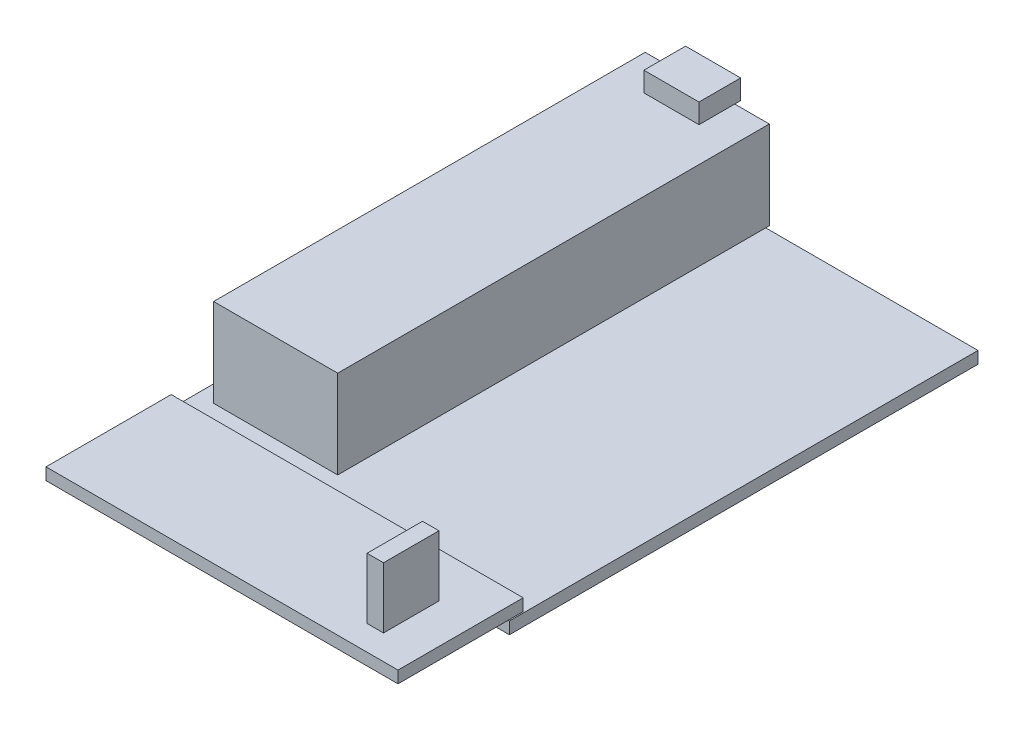
SolidWorks part; units mm, degrees
ref_plane "Front Plane" through (0, 0, 0) normal (0, 0, 1) x (1, 0, 0)
ref_plane "Top Plane" through (0, 0, 0) normal (0, 1, 0) x (1, 0, 0)
ref_plane "Right Plane" through (0, 0, 0) normal (1, 0, 0) x (0, 0, -1)
sketch "Sketch1" plane through (0, 0, 0) normal (0, 1, 0) x (1, 0, 0)
  line L1 (-42.6133, 31.1958) -> (7.5517, 31.1958)
  line L2 (-42.6133, 31.1958) -> (-42.6133, -35.3522)
  line L3 (-42.6133, -35.3522) -> (7.5517, -35.3522)
  line L4 (7.5517, 31.1958) -> (7.5517, -35.3522)
  dimension "D1" = 50.165
  dimension "D2" = 66.548
extrude "Boss-Extrude1" add sketch "Sketch1" along normal blind 1.7
sketch "Sketch2" plane through (0, 1.7, 0) normal (0, 1, 0) x (1, 0, 0)
  line L0 (-42.6133, 31.1958) -> (-42.6133, -35.3522) construction
  line L1 (-42.6133, -33.2186) -> (7.3751, -33.2186)
  line L2 (-42.6133, -33.2186) -> (-42.6133, -50.9986)
  line L3 (-42.6133, -50.9986) -> (7.3751, -50.9986)
  line L4 (7.3751, -33.2186) -> (7.3751, -50.9986)
  line L5 (-42.6133, -35.3522) -> (7.5517, -35.3522) construction
  dimension "D1" = 17.78
  dimension "D2" = 2.1336
extrude "Boss-Extrude2" add sketch "Sketch2" along normal blind 1.7
sketch "Sketch3" plane through (0, 1.7, 0) normal (0, 1, 0) x (1, 0, 0)
  line L0 (-42.6133, 31.1958) -> (-42.6133, -33.2186) construction
  line L1 (-40.2257, 31.7038) -> (-22.5981, 31.7038)
  line L2 (-40.2257, 31.7038) -> (-40.2257, -29.5864)
  line L3 (-40.2257, -29.5864) -> (-22.5981, -29.5864)
  line L4 (-22.5981, 31.7038) -> (-22.5981, -29.5864)
  line L5 (7.5517, 31.1958) -> (-42.6133, 31.1958) construction
  dimension "D1" = 2.3876
  dimension "D2" = 0.508
  dimension "D3" = 17.6276
  dimension "D4" = 61.2902
extrude "Boss-Extrude3" add sketch "Sketch3" along normal blind 12.5222 contours L2 L1 L4 L3
sketch "Sketch4" plane through (0, 14.2222, 0) normal (0, 1, 0) x (1, 0, 0)
  line L0 (-40.2257, 31.7038) -> (-22.5981, 31.7038) construction
  line L1 (-35.3235, 26.6238) -> (-27.5003, 26.6238)
  line L2 (-35.3235, 26.6238) -> (-35.3235, 32.542)
  line L3 (-35.3235, 32.542) -> (-27.5003, 32.542)
  line L4 (-27.5003, 26.6238) -> (-27.5003, 32.542)
  point P6 (-31.4119, 31.7038)
  point P7 (-31.4119, 26.6238)
  dimension "D1" = 7.8232
  dimension "D2" = 5.9182
  dimension "D3" = 0
  dimension "D4" = 0.8382
extrude "Boss-Extrude4" add sketch "Sketch4" along normal blind 2.794
sketch "Sketch5" plane through (0, 3.4, 0) normal (0, 1, 0) x (1, 0, 0)
  line L0 (-42.6133, -50.9986) -> (7.3751, -50.9986) construction
  line L1 (-0.5497, -39.594) -> (1.7871, -39.594)
  line L2 (-0.5497, -39.594) -> (-0.5497, -47.468)
  line L3 (-0.5497, -47.468) -> (1.7871, -47.468)
  line L4 (1.7871, -39.594) -> (1.7871, -47.468)
  line L5 (7.3751, -50.9986) -> (7.3751, -33.2186) construction
  dimension "D1" = 2.3368
  dimension "D2" = 7.874
  dimension "D3" = 3.5306
  dimension "D4" = 5.588
extrude "Boss-Extrude5" add sketch "Sketch5" along normal blind 8.636
